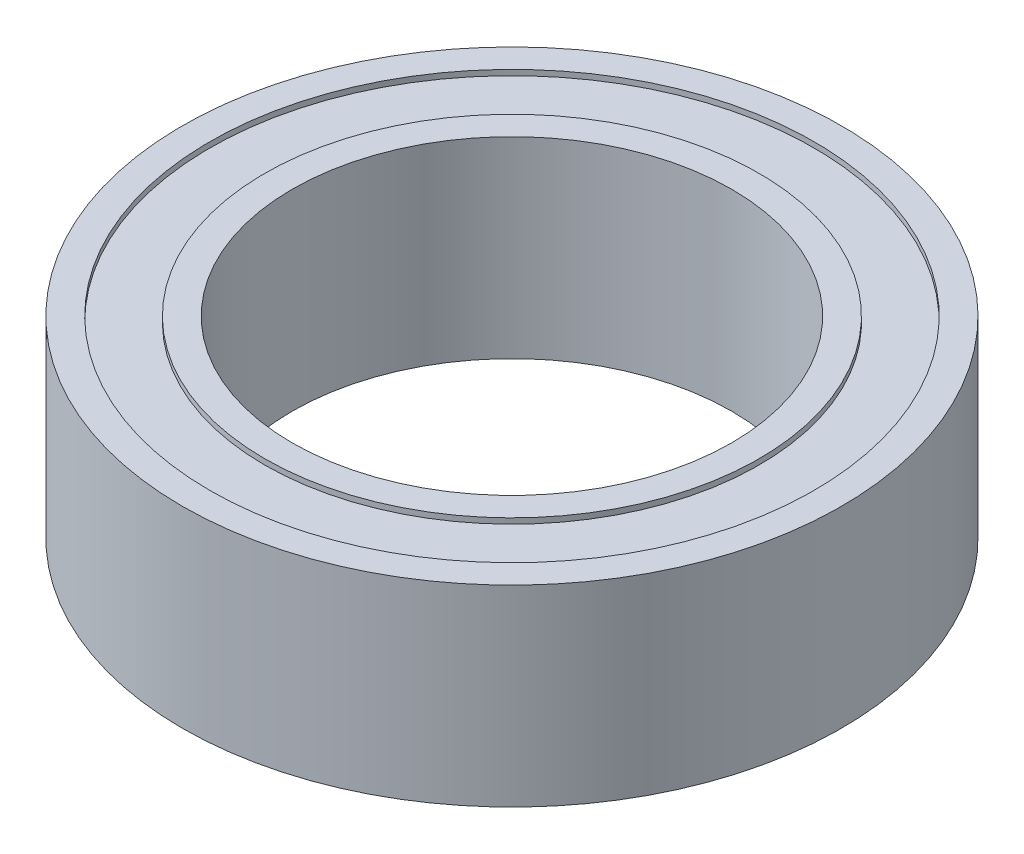
SolidWorks part; units mm, degrees
ref_plane "前视基准面" through (0, 0, 0) normal (0, 0, 1) x (1, 0, 0)
ref_plane "上视基准面" through (0, 0, 0) normal (0, 1, 0) x (1, 0, 0)
ref_plane "右视基准面" through (0, 0, 0) normal (1, 0, 0) x (0, 0, -1)
other "Configuration Table"
sketch "草图1" plane through (0, 0, 0) normal (0, 1, 0) x (1, 0, 0)
  circle A0 centre (0, 0) radius 6
  dimension "D1" = 12
extrude "凸台-拉伸1" add sketch "草图1" along normal blind 3.5
sketch "草图2" plane through (0, 3.5, 0) normal (0, 1, 0) x (1, 0, 0)
  circle A0 centre (0, 0) radius 4
  dimension "D1" = 8
extrude "切除-拉伸1" cut sketch "草图2" against normal up to next
sketch "草图3" plane through (0, 3.5, 0) normal (0, 1, 0) x (1, 0, 0)
  circle A0 centre (0, 0) radius 4.5
  circle A1 centre (0, 0) radius 5.5
  dimension "D1" = 11
  dimension "D2" = 9
extrude "切除-拉伸2" cut sketch "草图3" against normal blind 0.1
sketch "草图4" plane through (0, 0, 0) normal (0, -1, 0) x (1, 0, 0)
  circle A0 centre (0, 0) radius 5.5
  circle A1 centre (0, 0) radius 4.5
  dimension "D1" = 11
  dimension "D2" = 9
extrude "切除-拉伸3" cut sketch "草图4" against normal blind 0.1
